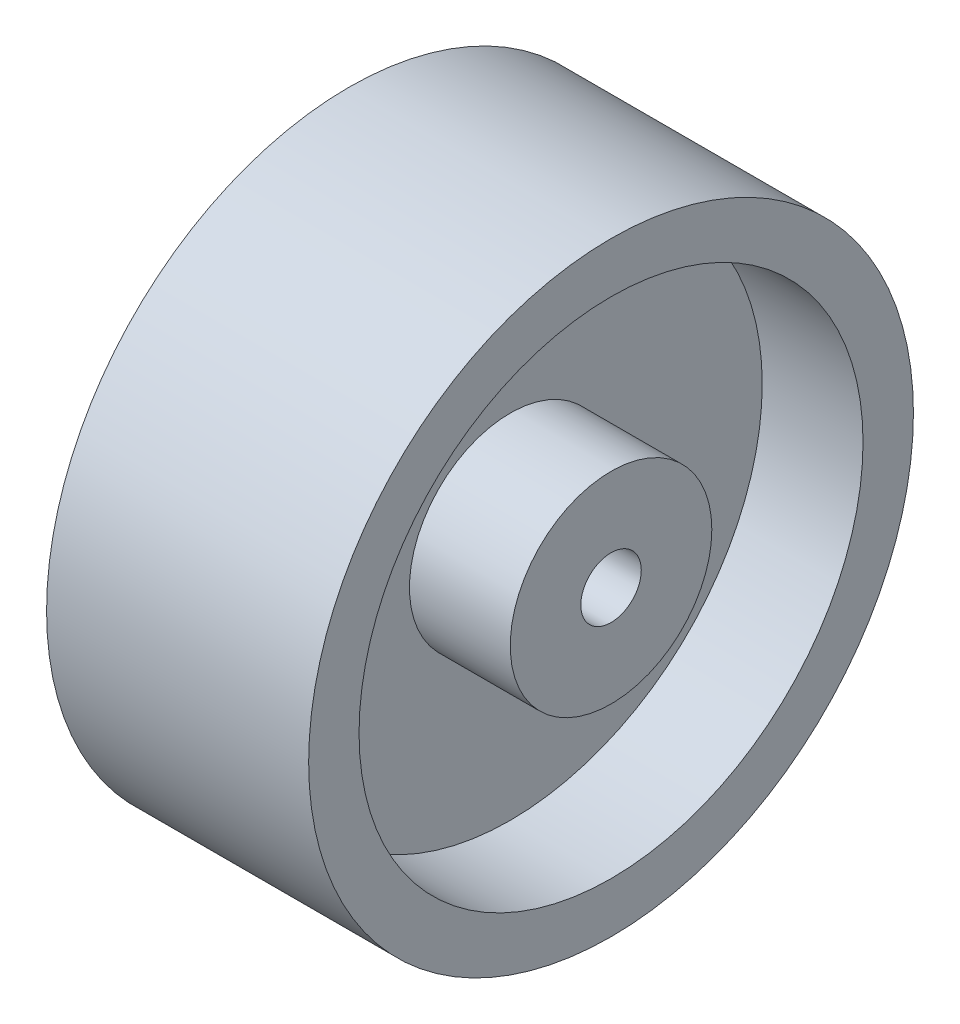
SolidWorks part; units mm, degrees
ref_plane "Front Plane" through (0, 0, 0) normal (0, 0, 1) x (1, 0, 0)
ref_plane "Top Plane" through (0, 0, 0) normal (0, 1, 0) x (1, 0, 0)
ref_plane "Right Plane" through (0, 0, 0) normal (1, 0, 0) x (0, 0, -1)
sketch "Sketch1" plane through (0, 0, 0) normal (1, 0, 0) x (0, 0, -1)
  circle A0 centre (0, 0) radius 30
  dimension "D1" = 60
extrude "Boss-Extrude1" add sketch "Sketch1" along normal blind 25 contours A0
sketch "Sketch2" plane through (0, 0, 0) normal (-1, 0, 0) x (0, 0, 1)
  line L0 (0, 0) -> (0, 25) construction
  line L1 (0, 25) -> (-4.0165, 24.6752)
  line L2 (-4.0165, 24.6752) -> (-2.3771, 4.3988)
  line L3 (4.0165, 24.6752) -> (2.3771, 4.3988)
  line L4 (0, 25) -> (4.0165, 24.6752)
  circle A0 centre (0, 0) radius 25
  circle A1 centre (0, 0) radius 5
  dimension "D1" = 50
  dimension "D2" = 10
extrude "Cut-Extrude1" cut sketch "Sketch2" against normal blind 5 contours L0 A1 L3 L4 | A1 L0 L1 L2 | L4 A0 | L1 A0
pattern_circular "CirPattern1" count 6 over 360 about axis through (0, -0.7528, 0) along (1, 0, 0) of "Cut-Extrude1"
sketch "Sketch3" plane through (25, 0, 0) normal (1, 0, 0) x (0, 0, -1)
  circle A0 centre (0, 0) radius 25
  circle A1 centre (0, 0) radius 10
  circle A2 centre (0, 0) radius 3
  dimension "D1" = 50
  dimension "D2" = 20
  dimension "D3" = 6
extrude "Cut-Extrude2" cut sketch "Sketch3" against normal blind 10 contours A0 A1 | A2
sketch "Sketch4" plane through (0, 0, 0) normal (-1, 0, 0) x (0, 0, 1)
  circle A0 centre (0, 0) radius 30
  circle A1 centre (0, 0) radius 27.0217
extrude "Boss-Extrude2" add sketch "Sketch4" along normal blind 1 contours A0
